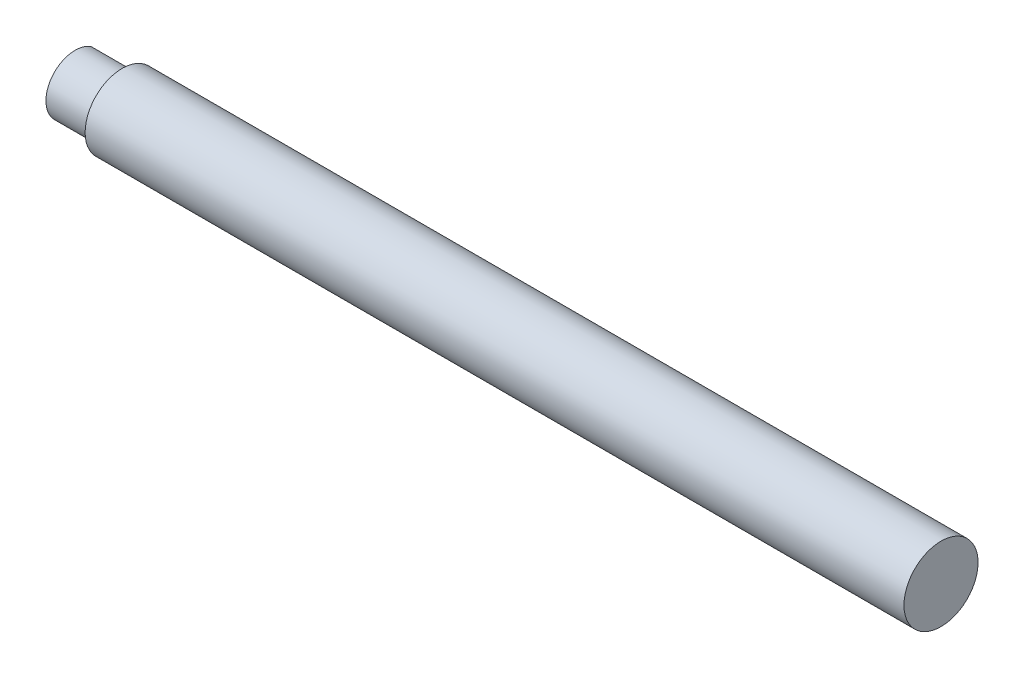
SolidWorks part; units mm, degrees
material "Plain Carbon Steel"
ref_plane "Front Plane" through (0, 0, 0) normal (0, 0, 1) x (1, 0, 0)
ref_plane "Top Plane" through (0, 0, 0) normal (0, 1, 0) x (1, 0, 0)
ref_plane "Right Plane" through (0, 0, 0) normal (1, 0, 0) x (0, 0, -1)
sketch "Sketch1" plane through (0, 0, 0) normal (1, 0, 0) x (0, 0, -1)
  circle A0 centre (0, 0) radius 2.5
  dimension "D1" = 5
extrude "Base" add sketch "Sketch1" along normal blind 58.42
sketch "Sketch2" plane through (0, 0, 0) normal (1, 0, 0) x (0, 0, -1)
  line L0 (1.0795, 1.6461) -> (1.0795, -1.6461)
  arc A0 (1.0795, 1.6461) -> (1.0795, -1.6461) centre (0, 0) ccw
  dimension "D1" = 3.937
  dimension "D2" = 1.0795
extrude "Cut-Extrude1" cut sketch "Sketch2" along normal blind 3.175 flip side to cut
